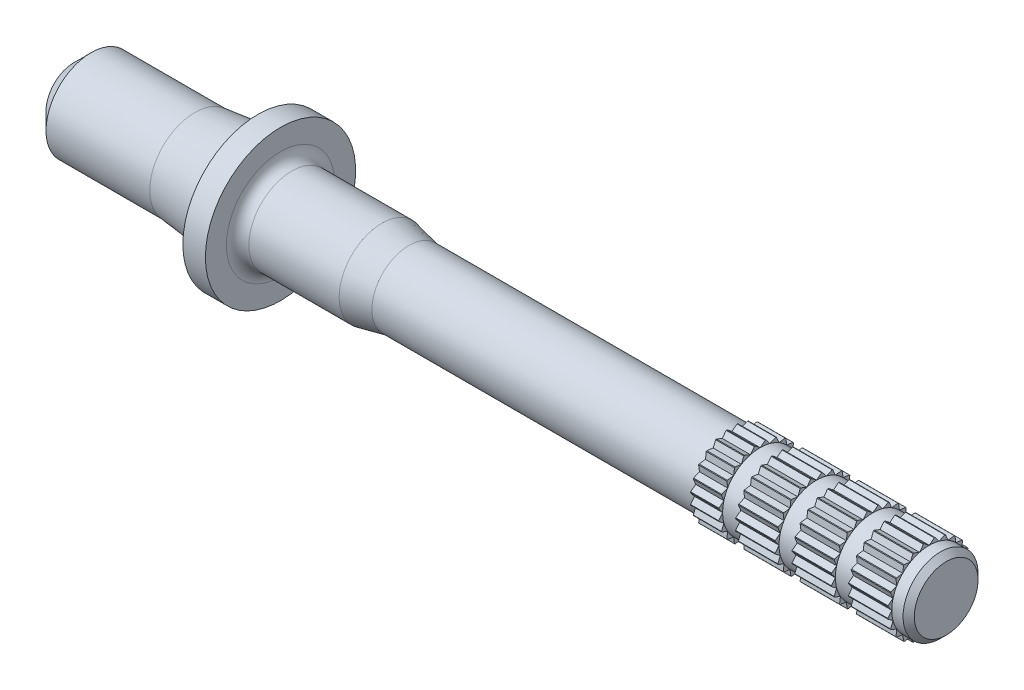
SolidWorks part; units mm, degrees
ref_plane "Front Plane" through (0, 0, 0) normal (0, 0, 1) x (1, 0, 0)
ref_plane "Top Plane" through (0, 0, 0) normal (0, 1, 0) x (1, 0, 0)
ref_plane "Right Plane" through (0, 0, 0) normal (1, 0, 0) x (0, 0, -1)
sketch "Sketch1" plane through (0, 0, 0) normal (0, 0, 1) x (1, 0, 0)
  line L0 (0, 0) -> (0, 2)
  line L1 (0, 2) -> (5.35, 2)
  line L2 (5.35, 2) -> (8.15, 2.3314)
  line L3 (8.15, 2.3314) -> (8.15, 3.3314)
  line L4 (8.15, 3.3314) -> (9.15, 3.3314)
  line L5 (9.15, 3.3314) -> (9.15, 1.9014)
  line L6 (9.15, 1.9014) -> (13.65, 1.9014)
  line L7 (13.65, 1.9014) -> (14.85, 1.6463)
  line L8 (14.85, 1.6463) -> (29.17, 1.6463)
  line L9 (29.17, 1.6463) -> (29.17, 1.85)
  line L13 (29.17, 1.85) -> (38.67, 1.85)
  line L14 (38.67, 1.85) -> (38.67, 0)
  line L16 (0, 0) -> (38.67, 0)
  dimension "D1" = 2
  dimension "D2" = 5.35
  dimension "D3" = 2.8
  dimension "D4" = 173.25
  dimension "D5" = 1
  dimension "D6" = 1
  dimension "D7" = 1.43
  dimension "D8" = 168
  dimension "D9" = 1.2
  dimension "D10" = 4.5
  dimension "D11" = 14.32
  dimension "D12" = 9.5
  dimension "D13" = 1.85
  dimension "D14" = 0.2037
revolve "Revolve1" add sketch "Sketch1" angle 360 about L16
sketch "Sketch2" plane through (38.67, 0, 0) normal (1, 0, 0) x (0, 0, -1)
  line L0 (0, 0) -> (0, 1.9014) construction
  line L1 (-0.225, 1.8363) -> (0, 1.6637)
  line L2 (0, 1.6637) -> (0.225, 1.8363)
  circle A0 centre (0, 0) radius 1.9014 construction
  circle A1 centre (0, 0) radius 1.85 construction
  arc A2 (-0.225, 1.8363) -> (0.225, 1.8363) centre (0, 0) cw
  dimension "D1" = 105
extrude "Cut-Extrude1" cut sketch "Sketch2" against normal up to next
pattern_circular "CirPattern1" count 24 over 360 about axis through (0, 0, 0) along (1, 0, 0) of "Cut-Extrude1"
sketch "Sketch3" plane through (38.67, 0, 0) normal (1, 0, 0) x (0, 0, -1)
  circle A0 centre (0, 0) radius 1.6637
extrude "Cut-Extrude2" cut sketch "Sketch3" against normal blind 0.75 flip side to cut
pattern_linear "LPattern1" count 4 spacing 2.5 along (-1, 0, 0) of "Cut-Extrude2"
chamfer "Chamfer1" distance 0.75 angle 45 1 edges at (0, 0, 2)
chamfer "Chamfer2" distance 0.25 angle 45 1 edges at (38.67, 0, -1.6637)
fillet "Fillet1" radius 0.5 2 edges at (8.15, 0, 2.3314) (9.15, 0, 1.9014)
